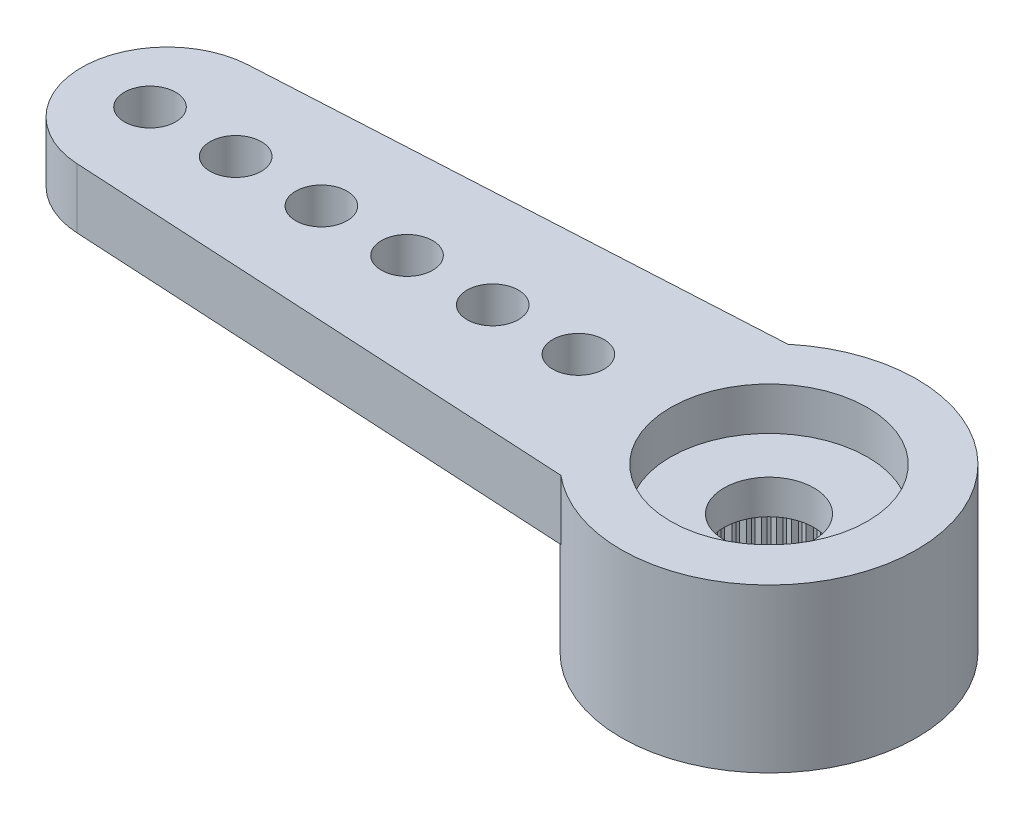
SolidWorks part; units mm, degrees
material "PVC Rígido"
ref_plane "Plano frontal" through (0, 0, 0) normal (0, 0, 1) x (1, 0, 0)
ref_plane "Plano superior" through (0, 0, 0) normal (0, 1, 0) x (1, 0, 0)
ref_plane "Plano direito" through (0, 0, 0) normal (1, 0, 0) x (0, 0, -1)
sketch "Esboço1" plane through (0, 0, 0) normal (0, 1, 0) x (1, 0, 0)
  line L0 (0, 0) -> (-14.05, 0) construction
  line L1 (-14.1591, 1.997) -> (-2.2091, 2.65)
  line L2 (-2.2091, -2.65) -> (-14.1591, -1.997)
  line L3 (0, 0) -> (-2.2091, 2.65) construction
  line L4 (0, 0) -> (-2.2091, -2.65) construction
  arc A0 (-2.2091, -2.65) -> (-2.2091, 2.65) centre (0, 0) ccw
  arc A1 (-14.1591, 1.997) -> (-14.1591, -1.997) centre (-14.05, 0) ccw
  dimension "D1" = 6.9
  dimension "D2" = 4
  dimension "D3" = 19.5
  dimension "D4" = 5.3
extrude "Ressalto-extrusão1" add sketch "Esboço1" against normal blind 1.4
sketch "Esboço2" plane through (0, -1.4, 0) normal (0, -1, 0) x (1, 0, 0)
  arc A0 (-2.2091, -2.65) -> (-2.2091, 2.65) centre (0, 0) ccw construction
  circle A1 centre (0, 0) radius 3.45
extrude "Ressalto-extrusão2" add sketch "Esboço2" along normal offset from surface (2.4 mm away) 3.8 up to face at (-7.242, 0, 0)
hole_wizard "Furo4" positions "Esboço9" profile "Esboço10" legacy end condition through all
sketch "Esboço9" plane through (0, 0, 0) normal (0, 1, 0) x (1, 0, 0)
  line L1 (-14.45, 0) -> (0, 0) construction
  arc A2 (-14.1591, 1.997) -> (-14.1591, -1.997) centre (-14.05, 0) ccw construction
  point P0 (-14.45, 0)
  point P19 (-16.05, 0)
  dimension "D1" = 1.6
sketch "Esboço10" plane through (-14.45, 0, 0) normal (1, 0, 0) x (0, 0, 1)
  line L0 (0, 0) -> (0, 3.8)
  line L1 (0, 3.8) -> (0.6, 3.8)
  line L2 (0.6, 3.8) -> (0.6, 0)
  line L3 (0.6, 0) -> (0, 0)
  line L4 (0, 110) -> (0, -10) construction
  dimension "Diameter" = 1.2
  dimension "Depth" = 3.8
pattern_linear "Padrão linear1" count 6 spacing 2 along (1, 0, 0) of "Furo4"
hole_wizard "Furo1" positions "Esboço3" profile "Esboço4" legacy
sketch "Esboço3" plane through (0, -3.8, 0) normal (0, -1, 0) x (-1, 0, 0)
  point P0 (0, 0)
sketch "Esboço4" plane through (0, -3.8, 0) normal (1, 0, 0) x (0, 0, -1)
  line L0 (0, 0) -> (0, 2)
  line L1 (0, 2) -> (2.475, 2)
  line L2 (2.475, 2) -> (2.475, 0)
  line L3 (2.475, 0) -> (0, 0)
  line L4 (0, 110) -> (0, -10) construction
  dimension "Diameter" = 4.95
  dimension "Depth" = 2
hole_wizard "Furo2" positions "Esboço5" profile "Esboço6" legacy
sketch "Esboço5" plane through (0, 0, 0) normal (0, 1, 0) x (1, 0, 0)
  point P0 (0, 0)
sketch "Esboço6" plane through (0, 0, 0) normal (1, 0, 0) x (0, 0, 1)
  line L0 (0, 0) -> (0, 1)
  line L1 (0, 1) -> (2.3, 1)
  line L2 (2.3, 1) -> (2.3, 0)
  line L3 (2.3, 0) -> (0, 0)
  line L4 (0, 110) -> (0, -10) construction
  dimension "Diameter" = 4.6
  dimension "Depth" = 1
hole_wizard "Furo3" positions "Esboço7" profile "Esboço8" legacy end condition through all
sketch "Esboço7" plane through (0, 0, 0) normal (0, 1, 0) x (1, 0, 0)
  point P0 (0, 0)
sketch "Esboço8" plane through (0, 0, 0) normal (1, 0, 0) x (0, 0, 1)
  line L0 (0, 0) -> (0, 3.8)
  line L1 (0, 3.8) -> (1.05, 3.8)
  line L2 (1.05, 3.8) -> (1.05, 0)
  line L3 (1.05, 0) -> (0, 0)
  line L4 (0, 110) -> (0, -10) construction
  dimension "Diameter" = 2.1
  dimension "Depth" = 3.8
sketch "Esboço11" plane through (0, -3.8, 0) normal (0, -1, 0) x (1, 0, 0)
  line L0 (-0.0981, 2.4731) -> (0, 2.375)
  line L1 (0, 2.375) -> (0.0981, 2.4731)
  line L2 (0, 0) -> (0, 2.475) construction
  circle A0 centre (0, 0) radius 2.375 construction
  circle A1 centre (0, 0) radius 2.475
  arc A2 (0.0981, 2.4731) -> (-0.0981, 2.4731) centre (0, 0) ccw
  dimension "D3" = 4.75
  dimension "D2" = 0.1
  dimension "D1" = 0
extrude "Ressalto-extrusão3" add sketch "Esboço11" against normal up to surface (2 mm away) up to face at (0, -1.8, 1.05)
pattern_circular "PadrãoCircular1" count 60 over 360 about axis through (0, 0, 0) along (0, 1, 0) of "Ressalto-extrusão3"
